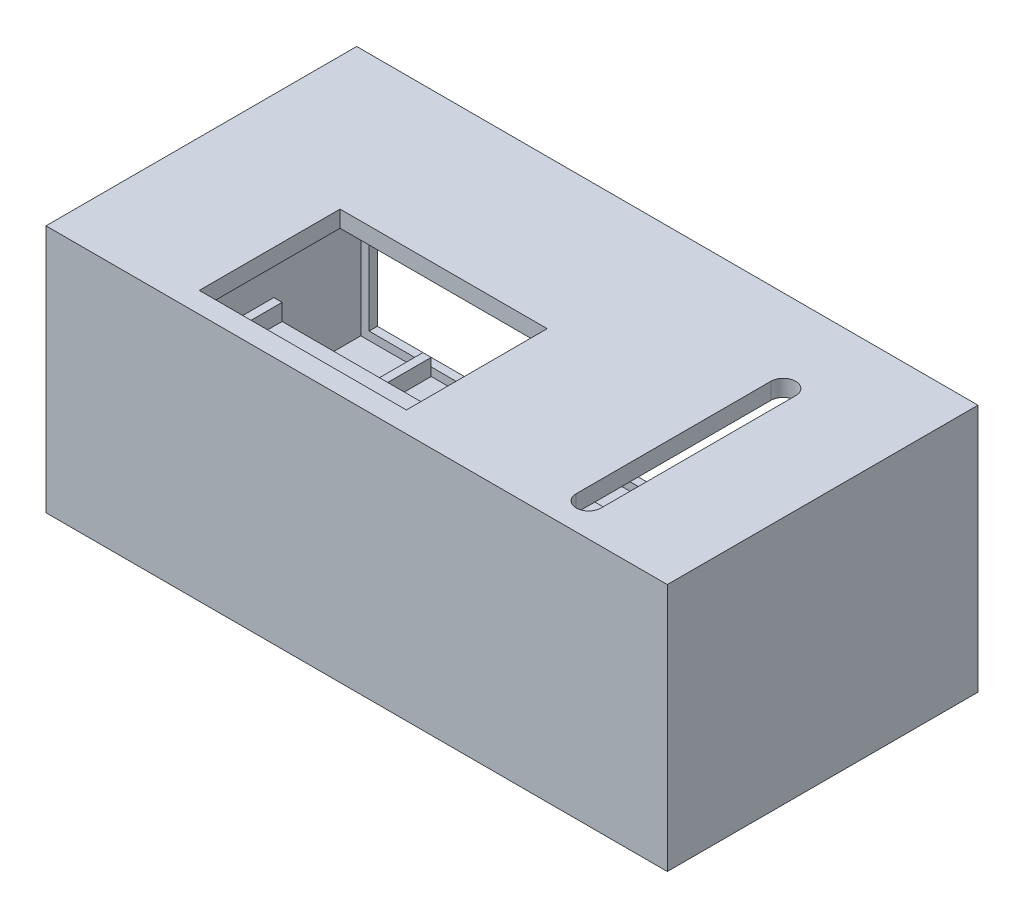
SolidWorks part; units mm, degrees
ref_plane "Plan de face" through (0, 0, 0) normal (0, 0, 1) x (1, 0, 0)
ref_plane "Plan de dessus" through (0, 0, 0) normal (0, 1, 0) x (1, 0, 0)
ref_plane "Plan de droite" through (0, 0, 0) normal (1, 0, 0) x (0, 0, -1)
sketch "Esquisse1" plane through (0, 0, 0) normal (0, 0, 1) x (1, 0, 0)
  line L1 (-75, -30) -> (75, -30)
  line L2 (-75, -30) -> (-75, 30)
  line L3 (-75, 30) -> (75, 30)
  line L4 (75, -30) -> (75, 30)
  line L5 (-75, -30) -> (75, 30) construction
  line L6 (-75, 30) -> (75, -30) construction
  point P0 (0, 0)
  dimension "D1" = 150
  dimension "D2" = 60
extrude "Boss.-Extru.1" add sketch "Esquisse1" along normal mid plane 75
sketch "Esquisse3" plane through (0, 0, -37.5) normal (0, 0, -1) x (-1, 0, 0)
  line L0 (75, 30) -> (75, -30) construction
  line L1 (-70, -26) -> (70, -26)
  line L2 (-70, -26) -> (-70, 26)
  line L3 (-70, 26) -> (70, 26)
  line L4 (70, -26) -> (70, 26)
  line L5 (-70, -26) -> (70, 26) construction
  line L6 (-70, 26) -> (70, -26) construction
  line L7 (-75, 30) -> (75, 30) construction
  point P0 (0, 0)
  dimension "D1" = 5
  dimension "D2" = 4
extrude "Enlèv. mat.-Extru.2" cut sketch "Esquisse3" against normal blind 70
sketch "Esquisse4" plane through (0, 0, -37.5) normal (0, 0, -1) x (-1, 0, 0)
  line L0 (0, 0) -> (56.2356, 0) construction
sketch "Esquisse6" plane through (-75, 0, 0) normal (-1, 0, 0) x (0, 0, 1)
  line L0 (37.5, 30) -> (37.5, -30) construction
  line L1 (2.5, -5) -> (32.5, -5)
  line L2 (2.5, -5) -> (2.5, 25)
  line L3 (2.5, 25) -> (32.5, 25)
  line L4 (32.5, -5) -> (32.5, 25)
  line L5 (2.5, -5) -> (32.5, 25) construction
  line L6 (2.5, 25) -> (32.5, -5) construction
  line L7 (37.5, 30) -> (-37.5, 30) construction
  point P0 (17.5, 10)
  dimension "D1" = 30
  dimension "D2" = 30
  dimension "D3" = 5
  dimension "D4" = 5
extrude "Enlèv. mat.-Ventilateur" cut sketch "Esquisse6" against normal up to next
sketch "Esquisse7" plane through (0, 0, 32.5) normal (0, 0, -1) x (-1, 0, 0)
  line L0 (-70, -26) -> (70, -26) construction
  line L1 (55, -26) -> (53, -26)
  line L2 (55, -26) -> (55, -22)
  line L3 (55, -22) -> (53, -22)
  line L4 (53, -26) -> (53, -22)
  line L5 (70, -26) -> (70, 26) construction
  dimension "D1" = 4
  dimension "D2" = 2
  dimension "D3" = 15
extrude "Boss.-Extru.2" add sketch "Esquisse7" along normal blind 66
sketch "Esquisse9" plane through (0, 0, 32.5) normal (0, 0, -1) x (-1, 0, 0)
  line L0 (-70, 3.5) -> (53, 3.5)
  line L1 (-70, 26) -> (-70, -26) construction
  line L2 (-70, 3.5) -> (-70, 0)
  line L3 (0, 0) -> (56.2356, 0) construction
  line L4 (55, 0) -> (-70, 0)
  line L5 (-70, 26) -> (-70, -26) construction
  line L6 (55, 0) -> (55, 7.5)
  line L7 (55, 7.5) -> (53, 7.5)
  line L8 (53, 7.5) -> (53, 3.5)
  line L9 (53, -22) -> (53, -26) construction
  dimension "D1" = 2
  dimension "D2" = 4
  dimension "D3" = 3.5
extrude "Boss.-Extru.3" add sketch "Esquisse9" along normal blind 30
sketch "Esquisse10" plane through (0, 0, 2.5) normal (0, 0, -1) x (-1, 0, 0)
  line L0 (53, 7.5) -> (53, 33.0886) construction
sketch "Esquisse11" plane through (0, 30, 0) normal (0, 1, 0) x (1, 0, 0)
  line L0 (75, -37.5) -> (-75, -37.5) construction
  line L1 (-43, 1.5) -> (7, 1.5)
  line L2 (-43, 1.5) -> (-43, -32.5)
  line L3 (-43, -32.5) -> (7, -32.5)
  line L4 (7, 1.5) -> (7, -32.5)
  line L5 (-75, -37.5) -> (-75, 37.5) construction
  dimension "D1" = 50
  dimension "D2" = 34
  dimension "D3" = 5
  dimension "D4" = 32
extrude "Enlèv. mat.-ecran" cut sketch "Esquisse11" against normal up to next
sketch "Esquisse12" plane through (0, 0, -37.5) normal (0, 0, -1) x (-1, 0, 0)
  line L0 (-70, 26) -> (-64, 26) construction
  line L1 (70, 26) -> (-70, 26) construction
  dimension "D1" = 6
sketch "Esquisse14" plane through (0, 30, 0) normal (0, 1, 0) x (1, 0, 0)
  line L0 (48, 37.5) -> (48, -37.5) construction
  line L1 (70, 37.5) -> (64, 37.5) construction
  line L2 (75, -37.5) -> (-75, -37.5) construction
  line L3 (48, 17.5) -> (48, -29.5) construction
  line L4 (51, 17.5) -> (51, -29.5)
  line L5 (45, 17.5) -> (45, -29.5)
  arc A0 (51, 17.5) -> (45, 17.5) centre (48, 17.5) ccw
  arc A1 (45, -29.5) -> (51, -29.5) centre (48, -29.5) ccw
  point P8 (48, -6)
  point P13 (0, 0)
  dimension "D1" = 3
  dimension "D2" = 16
  dimension "D3" = 47
  dimension "D4" = 20
extrude "Enlèv. mat.-molette" cut sketch "Esquisse14" against normal up to surface (4 mm away) up to face at (-9, 26, 6.5)
sketch "Esquisse15" plane through (-75, 0, 0) normal (-1, 0, 0) x (0, 0, 1)
  line L0 (-37.5, 30) -> (-37.5, -30) construction
  line L1 (-35.5, -28) -> (-33.5, -28)
  line L2 (-35.5, -28) -> (-35.5, 28)
  line L3 (-35.5, 28) -> (-33.5, 28)
  line L4 (-33.5, -28) -> (-33.5, 28)
  line L5 (-35.5, -28) -> (-33.5, 28) construction
  line L6 (-35.5, 28) -> (-33.5, -28) construction
  line L7 (37.5, 30) -> (-37.5, 30) construction
  point P0 (-34.5, 0)
  dimension "D1" = 56
  dimension "D2" = 2
  dimension "D3" = 2
  dimension "D4" = 2
extrude "Enlèv. mat.-paroi" cut sketch "Esquisse15" against normal blind 147
sketch "Esquisse16" plane through (0, 3.5, 0) normal (0, 1, 0) x (1, 0, 0)
  line L2 (64, -32.5) -> (64, -12.5)
  line L3 (64, -12.5) -> (32, -12.5)
  line L4 (32, -32.5) -> (32, -12.5)
  line L5 (30, -32.5) -> (32, -32.5)
  line L6 (66, -32.5) -> (64, -32.5)
  line L8 (75, -37.5) -> (75, 37.5) construction
  line L9 (66, -32.5) -> (66, -10.5)
  line L10 (66, -10.5) -> (30, -10.5)
  line L11 (30, -32.5) -> (30, -10.5)
  line L12 (75, -37.5) -> (-75, -37.5) construction
  point P0 (48, -22.5)
  dimension "D1" = 5
  dimension "D2" = 32
  dimension "D3" = 27
  dimension "D4" = 11
  dimension "D6" = 5
  dimension "D5" = 2
extrude "Boss.-molette" add sketch "Esquisse16" along normal blind 2
equation "\"L\"= \"RD1@Annotations\""
equation "\"D1@Enlèv. mat.-Paroi\"= \"L\" - 3"
